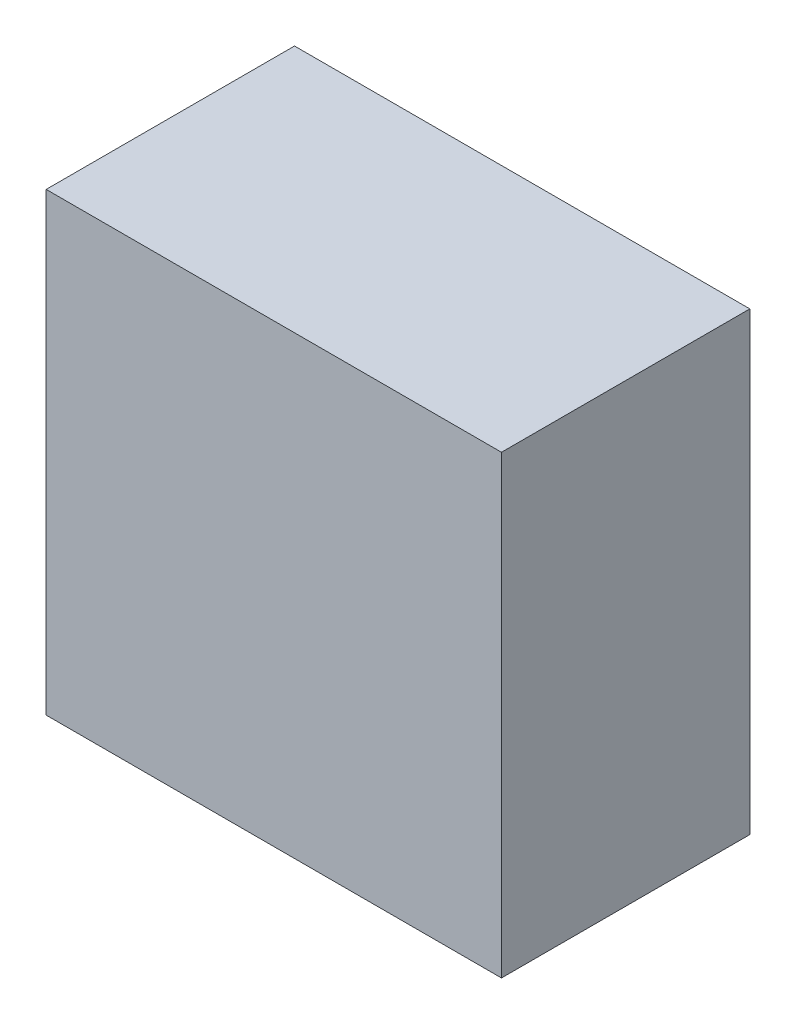
SolidWorks part; units mm, degrees
ref_plane "Plan de face" through (0, 0, 0) normal (0, 0, 1) x (1, 0, 0)
ref_plane "Plan de dessus" through (0, 0, 0) normal (0, 1, 0) x (1, 0, 0)
ref_plane "Plan de droite" through (0, 0, 0) normal (1, 0, 0) x (0, 0, -1)
sketch "Esquisse1" plane through (0, 0, 0) normal (0, 0, 1) x (1, 0, 0)
  line L1 (-11, 11) -> (11, 11)
  line L2 (-11, 11) -> (-11, -11)
  line L3 (-11, -11) -> (11, -11)
  line L4 (11, 11) -> (11, -11)
  line L5 (-11, 11) -> (11, -11) construction
  line L6 (-11, -11) -> (11, 11) construction
  point P0 (0, 0)
  dimension "D1" = 22
  dimension "D2" = 22
extrude "Boss.-Extru.1" add sketch "Esquisse1" along normal blind 12
